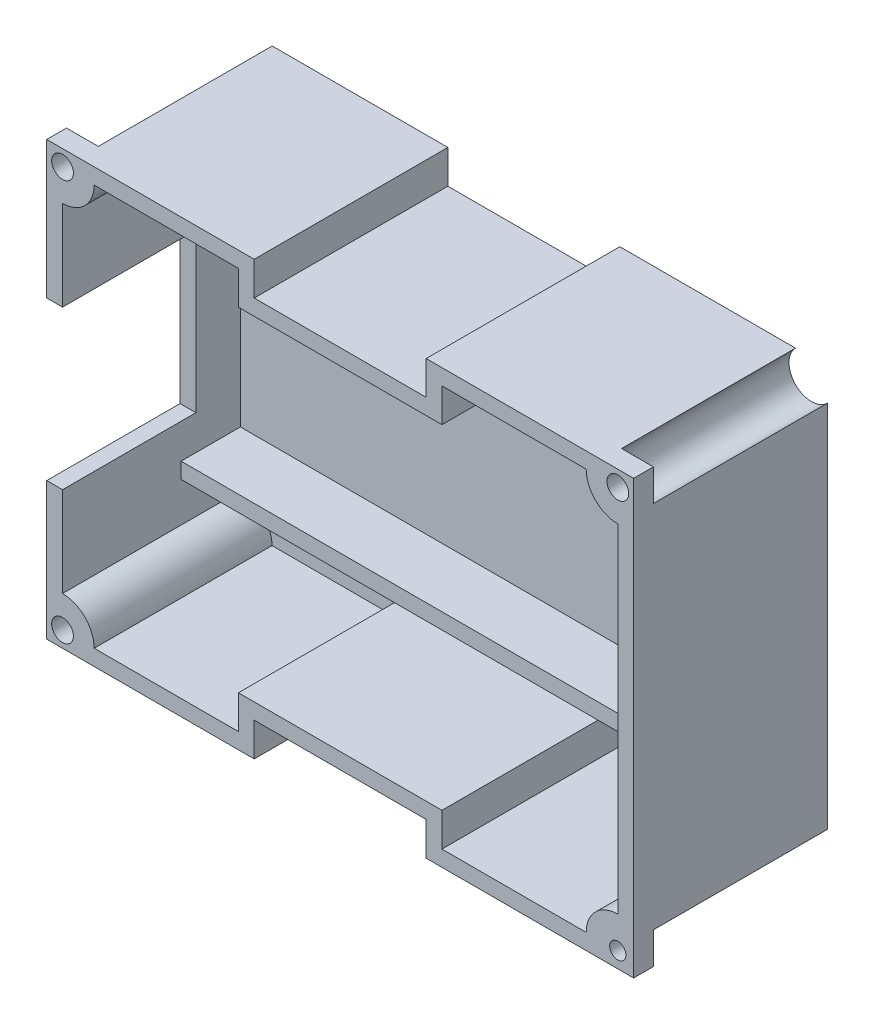
SolidWorks part; units mm, degrees
ref_plane "Front Plane" through (0, 0, 0) normal (0, 0, 1) x (1, 0, 0)
ref_plane "Top Plane" through (0, 0, 0) normal (0, 1, 0) x (1, 0, 0)
ref_plane "Right Plane" through (0, 0, 0) normal (1, 0, 0) x (0, 0, -1)
sketch "Sketch1" plane through (0, 0, 0) normal (0, 0, 1) x (1, 0, 0)
  line L0 (-38.4, 43.8) -> (-38.4, 40.4)
  line L1 (0, 0) -> (-21, 0)
  line L2 (0, 0) -> (0, 43.8)
  line L3 (0, 43.8) -> (-21, 43.8)
  line L4 (-59.4, 0) -> (-59.4, 43.8)
  line L5 (-21, 43.8) -> (-21, 40.4)
  line L6 (-38.4, 3.4) -> (-21, 3.4)
  line L7 (-38.4, 40.4) -> (-21, 40.4)
  line L8 (-38.4, 43.8) -> (-59.4, 43.8)
  line L9 (-38.4, 0) -> (-59.4, 0)
  line L10 (-21, 3.4) -> (-21, 0)
  line L11 (-38.4, 3.4) -> (-38.4, 0)
  dimension "D1" = 59.4
  dimension "D2" = 43.8
  dimension "D3" = 43.8
  dimension "D4" = 21
  dimension "D5" = 21
  dimension "D6" = 37
  dimension "D7" = 3.4
extrude "Boss-Extrude1" add sketch "Sketch1" along normal blind 1.6
sketch "Sketch2" plane through (0, 0, 1.6) normal (0, 0, 1) x (1, 0, 0)
  line L1 (-59.4, 43.8) -> (-38.4, 43.8)
  line L2 (-59.4, 43.8) -> (-59.4, 0)
  line L3 (-59.4, 0) -> (-38.4, 0)
  line L4 (0, 43.8) -> (0, 0)
  line L5 (-54.6, 42.2) -> (-40, 42.2)
  line L6 (-57.8, 39) -> (-57.8, 4.8)
  line L7 (-54.6, 1.6) -> (-40, 1.6)
  line L8 (-1.6, 39) -> (-1.6, 4.8)
  line L9 (-19.4, 42.2) -> (-19.4, 38.8)
  line L11 (-21, 3.4) -> (-21, 0) construction
  line L13 (-38.4, 40.4) -> (-38.4, 43.8)
  line L14 (-38.4, 40.4) -> (-21, 40.4)
  line L15 (-21, 40.4) -> (-21, 43.8)
  line L17 (-38.4, 0) -> (-38.4, 3.4)
  line L18 (-38.4, 3.4) -> (-21, 3.4)
  line L19 (-21, 3.4) -> (-21, 0)
  line L20 (-40, 5) -> (-19.4, 5)
  line L21 (-19.4, 38.8) -> (-40, 38.8)
  line L22 (-19.4, 5) -> (-19.4, 1.6)
  line L23 (-40, 5) -> (-40, 1.6)
  line L24 (-21, 0) -> (0, 0)
  line L25 (-19.4, 1.6) -> (-4.8, 1.6)
  line L26 (-19.4, 42.2) -> (-4.8, 42.2)
  line L27 (-21, 43.8) -> (0, 43.8)
  line L28 (-40, 42.2) -> (-40, 38.8)
  arc A4 (-57.8, 39) -> (-54.6, 42.2) centre (-57.8, 42.2) ccw
  arc A5 (-4.8, 42.2) -> (-1.6, 39) centre (-1.6, 42.2) ccw
  arc A6 (-1.6, 4.8) -> (-4.8, 1.6) centre (-1.6, 1.6) ccw
  arc A7 (-54.6, 1.6) -> (-57.8, 4.8) centre (-57.8, 1.6) ccw
  circle A8 centre (-57.8, 1.6) radius 1.1
  circle A9 centre (-57.8, 42.2) radius 1.1
  circle A10 centre (-1.6, 42.2) radius 1.1
  circle A11 centre (-1.6, 1.6) radius 0.8224
  point P45 (0, 0)
  dimension "D6" = 3.2
  dimension "D9" = 3.2
  dimension "D10" = 3.2
  dimension "D11" = 3.2
  dimension "D1" = 1.6
  dimension "D2" = 1.6
  dimension "D3" = 1.6
  dimension "D4" = 1.6
  dimension "D5" = 1.6
  dimension "D7" = 1.6
  dimension "D8" = 1.6
extrude "Boss-Extrude2" add sketch "Sketch2" along normal blind 18
sketch "Sketch4" plane through (0, 0, 19.6) normal (0, 0, 1) x (1, 0, 0)
  circle A0 centre (-57.8, 42.2) radius 2.275
  circle A1 centre (-1.6, 42.2) radius 2.275
  circle A2 centre (-57.8, 1.6) radius 2.275
  circle A3 centre (-1.6, 1.6) radius 2.275
  dimension "D1" = 4.55
  dimension "D2" = 4.55
  dimension "D3" = 4.55
  dimension "D4" = 4.55
extrude "Cut-Extrude1" cut sketch "Sketch4" against normal blind 18 from offset 2 offset against normal yes
sketch "Sketch5" plane through (-59.4, 0, 0) normal (-1, 0, 0) x (0, 0, 1)
  line L0 (19.6, 43.8) -> (19.6, 0) construction
  line L1 (19.6, 29.9) -> (6.1, 29.9)
  line L2 (19.6, 29.9) -> (19.6, 13.9)
  line L3 (19.6, 13.9) -> (6.1, 13.9)
  line L4 (6.1, 29.9) -> (6.1, 13.9)
  line L5 (19.6, 43.8) -> (17.6, 43.8) construction
  dimension "D1" = 16
  dimension "D2" = 13.5
  dimension "D3" = 13.9
extrude "Cut-Extrude2" cut sketch "Sketch5" against normal blind 18
sketch "Sketch6" plane through (0, 0, 1.6) normal (0, 0, 1) x (1, 0, 0)
  line L0 (-57.8, 39) -> (-57.8, 4.8) construction
  line L1 (-57.8, 33.4) -> (-3.8, 33.4)
  line L2 (-57.8, 33.4) -> (-57.8, 35)
  line L3 (-57.8, 35) -> (-1.6, 35)
  line L5 (-1.6, 4.8) -> (-1.6, 39) construction
  line L6 (-1.6, 4.8) -> (-1.6, 39) construction
  line L7 (-1.6, 8.8) -> (-3.8, 8.8)
  line L9 (-13.2666, 10.4) -> (-57.8, 10.4)
  line L10 (-57.8, 8.8) -> (-57.8, 10.4)
  line L20 (-3.8, 33.4) -> (-3.8, 10.4)
  line L21 (-1.6, 35) -> (-1.6, 8.8)
  line L25 (-57.8, 13.9) -> (-59.4, 13.9) construction
  line L26 (-13.2666, 8.8) -> (-13.2666, 10.4)
  line L27 (-3.8, 10.4) -> (-3.8, 8.8)
  line L28 (-13.2666, 8.8) -> (-57.8, 8.8)
  dimension "D1" = 23
  dimension "D2" = 1.6
  dimension "D3" = 1.6
  dimension "D4" = 3.5
  dimension "D5" = 54
extrude "Boss-Extrude3" add sketch "Sketch6" along normal blind 6
